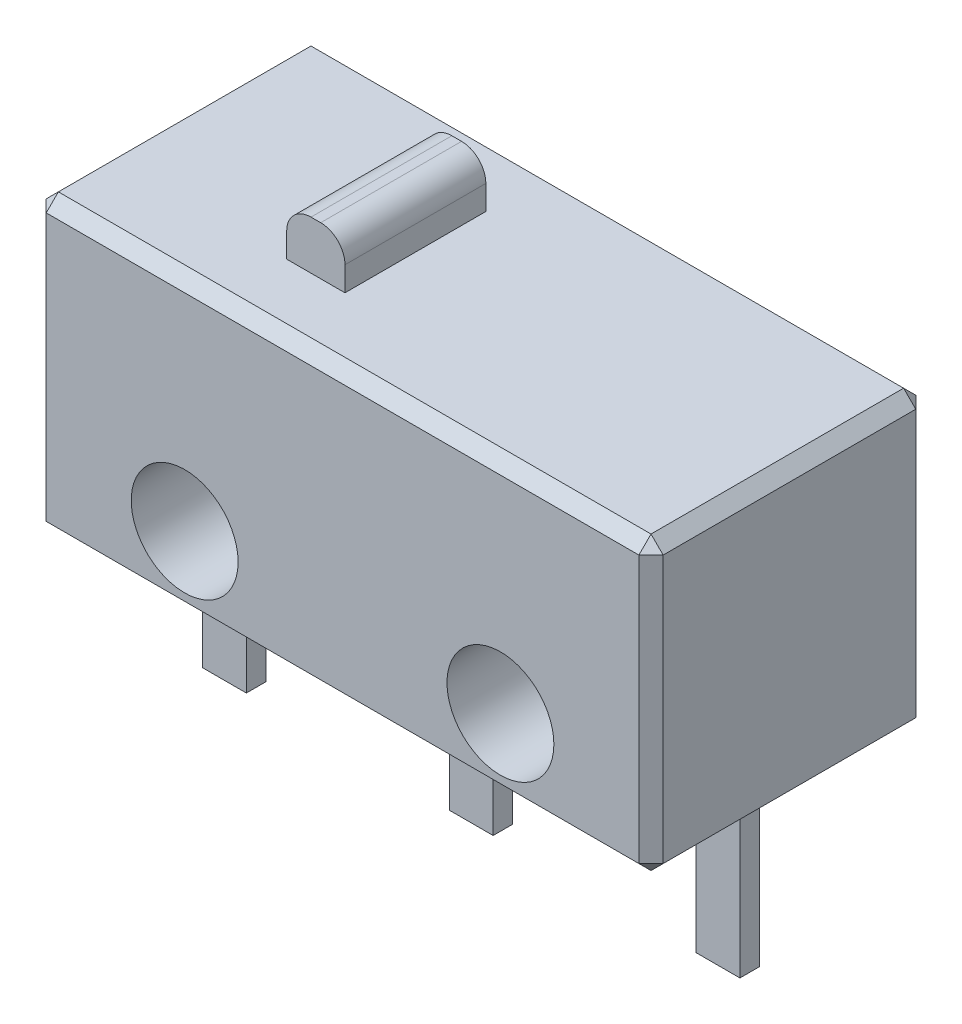
SolidWorks part; units mm, degrees
ref_plane "Piano frontale" through (0, 0, 0) normal (0, 0, 1) x (1, 0, 0)
ref_plane "Piano superiore" through (0, 0, 0) normal (0, 1, 0) x (1, 0, 0)
ref_plane "Piano destro" through (0, 0, 0) normal (1, 0, 0) x (0, 0, -1)
sketch "Schizzo1" plane through (0, 0, 0) normal (0, 0, 1) x (1, 0, 0)
  line L1 (-6.35, -3) -> (6.35, -3)
  line L2 (-6.35, -3) -> (-6.35, 3)
  line L3 (-6.35, 3) -> (6.35, 3)
  line L4 (6.35, -3) -> (6.35, 3)
  line L5 (-6.35, -3) -> (6.35, 3) construction
  line L6 (-6.35, 3) -> (6.35, -3) construction
  point P0 (0, 0)
  dimension "D1" = 12.7
  dimension "D2" = 6
extrude "Estrusione-Estrusione1" add sketch "Schizzo1" along normal blind 5.7
sketch "Schizzo2" plane through (0, 3, 0) normal (0, 1, 0) x (1, 0, 0)
  line L1 (-2.55, -4.3) -> (-1.35, -4.3)
  line L2 (-2.55, -4.3) -> (-2.55, -1.4)
  line L3 (-2.55, -1.4) -> (-1.35, -1.4)
  line L4 (-1.35, -4.3) -> (-1.35, -1.4)
  line L5 (-2.55, -4.3) -> (-1.35, -1.4) construction
  line L6 (-2.55, -1.4) -> (-1.35, -4.3) construction
  line L7 (6.35, -5.7) -> (-6.35, -5.7) construction
  point P0 (-1.95, -2.85)
  dimension "D1" = 1.2
  dimension "D2" = 2.9
  dimension "D3" = 2.85
  dimension "D4" = 1.95
extrude "Estrusione-Estrusione2" add sketch "Schizzo2" along normal blind 1
sketch "Schizzo3" plane through (0, 0, 5.7) normal (0, 0, 1) x (1, 0, 0)
  line L0 (6.35, 3) -> (-6.35, 3) construction
  circle A0 centre (-3.25, -1.5) radius 1.1
  circle A1 centre (3.25, -1.5) radius 1.1
  dimension "D1" = 6.5
  dimension "D2" = 3.25
  dimension "D3" = 4.5
extrude "Taglio-Estrusione1" cut sketch "Schizzo3" against normal through all
fillet "Raccordo1" radius 0.5 2 edges at (-1.35, 4, 2.85) (-2.55, 4, 2.85)
sketch "Schizzo4" plane through (0, -3, 0) normal (0, -1, 0) x (1, 0, 0)
  line L0 (-6.35, 2.85) -> (6.35, 2.85) construction
  line L1 (-0.45, 3.05) -> (0.45, 3.05)
  line L2 (-0.45, 3.05) -> (-0.45, 2.65)
  line L3 (-0.45, 2.65) -> (0.45, 2.65)
  line L4 (0.45, 3.05) -> (0.45, 2.65)
  line L5 (-0.45, 3.05) -> (0.45, 2.65) construction
  line L6 (-0.45, 2.65) -> (0.45, 3.05) construction
  line L7 (-6.35, 5.7) -> (-6.35, 0) construction
  line L8 (6.35, 5.7) -> (6.35, 0) construction
  point P0 (0, 2.85)
  dimension "D1" = 0.9
  dimension "D2" = 0.4
extrude "Estrusione-Estrusione3" add sketch "Schizzo4" along normal blind 3.4
pattern_linear "Ripetizione a L1" count 2 spacing 5.08 along (1, 0, 0) count 2 spacing 5.08 along (-1, 0, 0) of "Estrusione-Estrusione3"
chamfer "Smusso1" distance 0.25 angle 45 24 edges at (0, -3, 5.7) (0, -3, 0) (6.35, -3, 2.85) (6.35, 0, 5.7) (6.35, 3, 2.85) (6.35, 0, 0) (-6.35, 3, 2.85) (0, 3, 0) (-6.35, 0, 0) (-6.35, -3, 2.85) (-6.35, 0, 5.7) (0, 3, 5.7) (-5.08, -3, 3.05) (-5.53, -3, 2.85) (-5.08, -3, 2.65) (-4.63, -3, 2.85) (0, -3, 3.05) (-0.45, -3, 2.85) (0, -3, 2.65) (0.45, -3, 2.85) (5.08, -3, 3.05) (4.63, -3, 2.85) (5.08, -3, 2.65) (5.53, -3, 2.85)
equation "\"D2@Schizzo3\"=\"D1@Schizzo3\"/2"
